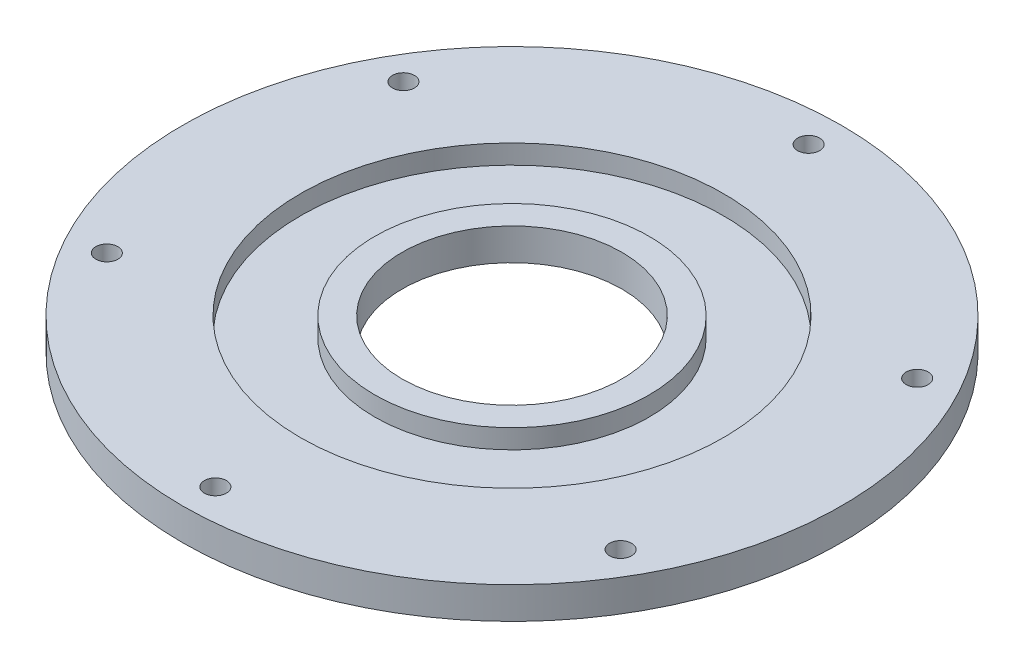
SolidWorks part; units mm, degrees
ref_plane "Front Plane" through (0, 0, 0) normal (0, 0, 1) x (1, 0, 0)
ref_plane "Top Plane" through (0, 0, 0) normal (0, 1, 0) x (1, 0, 0)
ref_plane "Right Plane" through (0, 0, 0) normal (1, 0, 0) x (0, 0, -1)
sketch "Sketch1" plane through (0, 0, 0) normal (0, 1, 0) x (1, 0, 0)
  circle A0 centre (0, 0) radius 60
  circle A1 centre (0, 0) radius 20
  dimension "D1" = 120
  dimension "D2" = 40
extrude "Boss-Extrude1" add sketch "Sketch1" along normal blind 5.8
sketch "Sketch2" plane through (0, 5.8, 0) normal (0, 1, 0) x (1, 0, 0)
  circle A0 centre (0, 0) radius 25
  circle A1 centre (0, 0) radius 38.5
  dimension "D1" = 50
  dimension "D2" = 77
extrude "Cut-Extrude1" cut sketch "Sketch2" against normal blind 3.5
sketch "Sketch3" plane through (0, 5.8, 0) normal (0, 1, 0) x (1, 0, 0)
  circle A0 centre (0, 0) radius 54 construction
  circle A1 centre (0, 54) radius 2
  circle A2 centre (46.7654, 27) radius 2
  circle A3 centre (46.7654, -27) radius 2
  circle A4 centre (0, -54) radius 2
  circle A5 centre (-46.7654, -27) radius 2
  circle A6 centre (-46.7654, 27) radius 2
  point P17 (0, 0)
  dimension "D1" = 108
  dimension "D2" = 4
  dimension "D3" = 6
extrude "Cut-Extrude2" cut sketch "Sketch3" against normal through all
